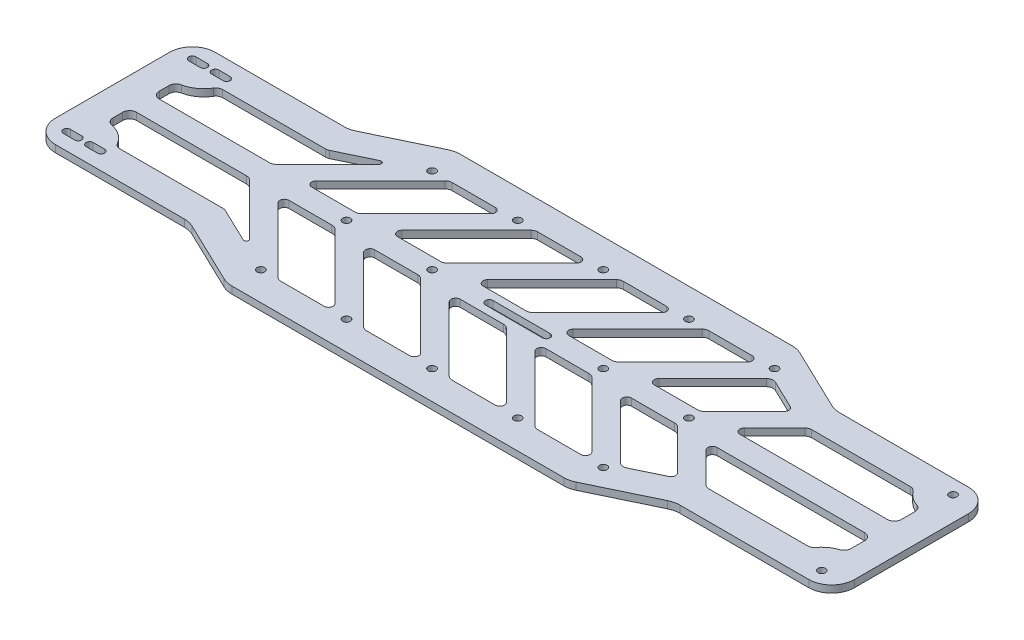
SolidWorks part; units mm, degrees
material "6061-T6 (SS)"
ref_plane "Front Plane" through (0, 0, 0) normal (0, 0, 1) x (1, 0, 0)
ref_plane "Top Plane" through (0, 0, 0) normal (0, 1, 0) x (1, 0, 0)
ref_plane "Right Plane" through (0, 0, 0) normal (1, 0, 0) x (0, 0, -1)
sketch "Sketch1" plane through (0, 0, 0) normal (0, 1, 0) x (1, 0, 0)
  line L1 (0, 0) -> (355.6, 0)
  line L2 (0, 0) -> (0, 101.6)
  line L3 (0, 101.6) -> (355.6, 101.6)
  line L4 (355.6, 0) -> (355.6, 101.6)
  dimension "D1" = 355.6
  dimension "D2" = 101.6
extrude "Boss-Extrude1" add sketch "Sketch1" along normal blind 3.175
sketch "Sketch2" plane through (0, 0, 0) normal (0, -1, 0) x (1, 0, 0)
  line L0 (0, -50.8) -> (355.6, -50.8) construction
  line L1 (0, -101.6) -> (0, 0) construction
  line L2 (355.6, 0) -> (355.6, -101.6) construction
  point P6 (10.16, -22.86)
  point P7 (344.8634, -21.59)
  point P8 (344.8634, -80.01)
  point P9 (10.16, -78.74)
  dimension "D1" = 55.88
  dimension "D2" = 58.42
  dimension "D3" = 334.7034
  dimension "D4" = 10.16
hole_wizard "M3 Clearance Hole2" positions "Sketch6" profile "Sketch5" hole size "M3" standard "ANSI Metric" end condition through all
sketch "Sketch6" plane through (0, 0, 0) normal (0, -1, 0) x (-1, 0, 0)
  point P0 (-344.8634, 21.59)
  point P3 (-344.8634, 80.01)
sketch "Sketch5" plane through (344.8634, 0, -21.59) normal (1, 0, 0) x (0, 0, -1)
  line L0 (0, 0) -> (0, 3.175)
  line L1 (0, 3.175) -> (1.7, 3.175)
  line L2 (1.7, 3.175) -> (1.7, 0)
  line L5 (1.7, 0) -> (0, 0)
  line L11 (0, -6.35) -> (0, 107.95) construction
  dimension "Thru Hole Dia." = 3.4
  dimension "Thru Hole Depth" = 3.175
sketch "Sketch7" plane through (0, 0, 0) normal (0, -1, 0) x (1, 0, 0)
  line L0 (7.62, -22.86) -> (12.7, -22.86) construction
  line L1 (7.62, -21.2838) -> (12.7, -21.2838)
  line L2 (7.62, -24.4362) -> (12.7, -24.4362)
  line L3 (0, -50.8) -> (34.1188, -50.8) construction
  line L4 (0, -50.8) -> (355.6, -50.8) construction
  line L5 (7.62, -78.74) -> (12.7, -78.74) construction
  line L6 (7.62, -80.3162) -> (12.7, -80.3162)
  line L7 (7.62, -77.1638) -> (12.7, -77.1638)
  arc A0 (7.62, -21.2838) -> (7.62, -24.4362) centre (7.62, -22.86) ccw
  arc A1 (12.7, -24.4362) -> (12.7, -21.2838) centre (12.7, -22.86) ccw
  arc A2 (7.62, -80.3162) -> (7.62, -77.1638) centre (7.62, -78.74) cw
  arc A3 (12.7, -77.1638) -> (12.7, -80.3162) centre (12.7, -78.74) cw
  point P2 (10.16, -22.86)
  point P15 (10.16, -78.74)
  dimension "D1" = 1.5762
  dimension "D2" = 5.08
extrude "Cut-Extrude1" cut sketch "Sketch7" against normal through all
sketch "Sketch16" plane through (0, 3.175, 0) normal (0, 1, 0) x (1, 0, 0)
  line L0 (355.6, 15.24) -> (285.75, 15.24)
  line L1 (355.6, 0) -> (355.6, 101.6) construction
  line L2 (0, 0) -> (355.6, 0) construction
  line L3 (355.6, 15.24) -> (355.6, 0)
  line L4 (355.6, 0) -> (254, 0)
  line L5 (285.75, 15.24) -> (254, 0)
  line L6 (355.6, 50.8) -> (0, 50.8) construction
  line L7 (0, 101.6) -> (0, 0) construction
  line L8 (177.8, 0) -> (177.8, 101.6) construction
  line L9 (355.6, 101.6) -> (0, 101.6) construction
  line L10 (69.85, 15.24) -> (101.6, 0)
  line L11 (0, 0) -> (101.6, 0)
  line L12 (0, 15.24) -> (0, 0)
  line L13 (0, 15.24) -> (69.85, 15.24)
  line L14 (0, 86.36) -> (69.85, 86.36)
  line L15 (0, 86.36) -> (0, 101.6)
  line L16 (0, 101.6) -> (101.6, 101.6)
  line L17 (69.85, 86.36) -> (101.6, 101.6)
  line L18 (285.75, 86.36) -> (254, 101.6)
  line L19 (355.6, 101.6) -> (254, 101.6)
  line L20 (355.6, 86.36) -> (355.6, 101.6)
  line L21 (355.6, 86.36) -> (285.75, 86.36)
  dimension "D1" = 15.24
  dimension "D2" = 101.6
  dimension "D3" = 69.85
extrude "Cut-Extrude3" cut sketch "Sketch16" against normal through all
fillet "Fillet1" radius 10.16 12 edges at (0, 1.5875, -86.36) (69.85, 1.5875, -86.36) (101.6, 1.5875, -101.6) (254, 1.5875, -101.6) (285.75, 1.5875, -86.36) (355.6, 1.5875, -86.36) (0, 1.5875, -15.24) (69.85, 1.5875, -15.24) (101.6, 1.5875, 0) (254, 1.5875, 0) (285.75, 1.5875, -15.24) (355.6, 1.5875, -15.24)
sketch "Sketch17" plane through (0, 3.175, 0) normal (0, 1, 0) x (1, 0, 0)
  line L0 (0, 50.8) -> (355.6, 50.8) construction
  line L1 (142.24, 88.9) -> (104.14, 50.8) construction
  line L2 (0, 50.8) -> (355.6, 50.8) construction
  line L3 (0, 76.2) -> (0, 25.4) construction
  line L4 (111.76, 88.9) -> (78.74, 55.88)
  line L5 (78.74, 55.88) -> (104.14, 55.88)
  line L6 (104.14, 55.88) -> (137.16, 88.9)
  line L7 (137.16, 88.9) -> (111.76, 88.9)
  line L8 (104.14, 88.9) -> (142.24, 88.9) construction
  line L9 (78.74, 45.72) -> (104.14, 45.72)
  line L10 (104.14, 45.72) -> (137.16, 12.7)
  line L11 (137.16, 12.7) -> (111.76, 12.7)
  line L12 (111.76, 12.7) -> (78.74, 45.72)
  line L13 (175.26, 88.9) -> (149.86, 88.9)
  line L14 (149.86, 88.9) -> (116.84, 55.88)
  line L15 (142.24, 55.88) -> (175.26, 88.9)
  line L16 (116.84, 55.88) -> (142.24, 55.88)
  line L17 (116.84, 45.72) -> (142.24, 45.72)
  line L18 (142.24, 45.72) -> (175.26, 12.7)
  line L19 (149.86, 12.7) -> (116.84, 45.72)
  line L20 (175.26, 12.7) -> (149.86, 12.7)
  line L21 (213.36, 88.9) -> (187.96, 88.9)
  line L22 (187.96, 88.9) -> (154.94, 55.88)
  line L23 (180.34, 55.88) -> (213.36, 88.9)
  line L24 (154.94, 55.88) -> (180.34, 55.88)
  line L25 (154.94, 45.72) -> (180.34, 45.72)
  line L26 (180.34, 45.72) -> (213.36, 12.7)
  line L27 (187.96, 12.7) -> (154.94, 45.72)
  line L28 (213.36, 12.7) -> (187.96, 12.7)
  line L29 (251.46, 88.9) -> (226.06, 88.9)
  line L30 (226.06, 88.9) -> (193.04, 55.88)
  line L31 (218.44, 55.88) -> (251.46, 88.9)
  line L32 (193.04, 55.88) -> (218.44, 55.88)
  line L33 (193.04, 45.72) -> (218.44, 45.72)
  line L34 (218.44, 45.72) -> (251.46, 12.7)
  line L35 (226.06, 12.7) -> (193.04, 45.72)
  line L36 (251.46, 12.7) -> (226.06, 12.7)
  line L37 (260.0411, 84.7811) -> (231.14, 55.88)
  line L38 (231.14, 55.88) -> (256.54, 55.88)
  line L39 (256.54, 55.88) -> (277.2032, 76.5432)
  line L40 (277.2032, 76.5432) -> (260.0411, 84.7811)
  line L41 (256.0844, 100.5995) -> (283.6656, 87.3605) construction
  line L42 (231.14, 45.72) -> (256.54, 45.72)
  line L43 (260.0411, 16.8189) -> (231.14, 45.72)
  line L44 (256.54, 45.72) -> (277.2032, 25.0568)
  line L45 (277.2032, 25.0568) -> (260.0411, 16.8189)
  line L46 (287.02, 73.66) -> (269.24, 55.88)
  line L47 (269.24, 55.88) -> (342.9, 55.88)
  line L48 (342.9, 55.88) -> (342.9, 67.4627)
  line L49 (287.02, 73.66) -> (333.8649, 73.66)
  line L51 (288.0621, 86.36) -> (345.44, 86.36) construction
  line L52 (355.6, 25.4) -> (355.6, 76.2) construction
  line L53 (269.24, 45.72) -> (342.9, 45.72)
  line L54 (342.9, 45.72) -> (342.9, 34.1373)
  line L55 (287.02, 27.94) -> (333.8649, 27.94)
  line L56 (287.02, 27.94) -> (269.24, 45.72)
  line L57 (12.7, 55.88) -> (66.04, 55.88)
  line L58 (66.04, 55.88) -> (86.36, 76.2)
  line L59 (72.7401, 73.66) -> (24.3397, 73.66)
  line L60 (12.7, 66.04) -> (12.7, 55.88)
  line L61 (10.16, 86.36) -> (67.5379, 86.36) construction
  line L62 (86.36, 76.2) -> (94.0476, 83.8876)
  line L63 (94.0476, 83.8876) -> (72.7401, 73.66)
  line L64 (71.9344, 87.3605) -> (99.5156, 100.5995) construction
  line L65 (12.7, 45.72) -> (66.04, 45.72)
  line L66 (86.36, 25.4) -> (94.0476, 17.7124)
  line L67 (66.04, 45.72) -> (86.36, 25.4)
  line L68 (94.0476, 17.7124) -> (72.7401, 27.94)
  line L69 (72.7401, 27.94) -> (24.3397, 27.94)
  line L70 (12.7, 35.56) -> (12.7, 45.72)
  arc A0 (342.9, 67.4627) -> (333.8649, 73.66) centre (344.8634, 80.01) cw
  circle A1 centre (344.8634, 80.01) radius 1.7 construction
  arc A2 (342.9, 34.1373) -> (333.8649, 27.94) centre (344.8634, 21.59) ccw
  arc A3 (24.3397, 73.66) -> (12.7, 66.04) centre (12.7, 78.74) cw
  arc A4 (12.7, 77.1638) -> (12.7, 80.3162) centre (12.7, 78.74) ccw construction
  arc A5 (24.3397, 27.94) -> (12.7, 35.56) centre (12.7, 22.86) ccw
  point P4 (104.14, 88.9)
  point P8 (104.14, 50.8)
  point P9 (104.14, 12.7)
  point P12 (142.24, 88.9)
  point P13 (142.24, 50.8)
  point P14 (142.24, 12.7)
  point P15 (180.34, 88.9)
  point P16 (180.34, 50.8)
  point P17 (180.34, 12.7)
  point P18 (218.44, 88.9)
  point P19 (218.44, 50.8)
  point P20 (218.44, 12.7)
  point P21 (256.54, 88.9)
  point P22 (256.54, 50.8)
  point P23 (256.54, 12.7)
  dimension "D13" = 12.7
  dimension "D17" = 12.7
  dimension "D1" = 38.1
  dimension "D2" = 104.14
  dimension "D4" = 45
  dimension "D5" = 5.08
  dimension "D6" = 25.4
  dimension "D7" = 7.62
  dimension "D9" = 38.1
  dimension "D10" = 38.1
  dimension "D11" = 12.7
  dimension "D12" = 12.7
  dimension "D14" = 12.7
  dimension "D15" = 12.7
  dimension "D16" = 38.1
  dimension "D18" = 12.7
  dimension "D19" = 38.1
  dimension "D3" = 5
  dimension "D8" = 4
hole_wizard "M3 Clearance Hole5" positions "Sketch19" profile "Sketch18" hole size "M3" standard "ANSI Metric" end condition through all
sketch "Sketch19" plane through (0, 3.175, 0) normal (0, 1, 0) x (1, 0, 0)
  point P0 (104.14, 88.9)
  point P3 (142.24, 88.9)
  point P6 (180.34, 88.9)
  point P9 (218.44, 88.9)
  point P12 (256.54, 88.9)
  point P15 (256.54, 12.7)
  point P18 (218.44, 12.7)
  point P21 (180.34, 12.7)
  point P24 (142.24, 12.7)
  point P27 (104.14, 12.7)
  point P30 (104.14, 50.8)
  point P33 (256.54, 50.8)
  point P36 (142.24, 50.8)
  point P39 (180.34, 50.8)
  point P42 (218.44, 50.8)
sketch "Sketch18" plane through (104.14, 3.175, -88.9) normal (1, 0, 0) x (0, 0, 1)
  line L0 (0, 0) -> (0, 3.175)
  line L1 (0, 3.175) -> (1.7, 3.175)
  line L2 (1.7, 3.175) -> (1.7, 0)
  line L5 (1.7, 0) -> (0, 0)
  line L11 (0, -6.35) -> (0, 107.95) construction
  dimension "Thru Hole Dia." = 3.4
  dimension "Thru Hole Depth" = 3.175
extrude "Cut-Extrude4" cut sketch "Sketch17" against normal through all
fillet "Fillet2" radius 2.032 16 edges at (137.16, 1.5875, -12.7) (175.26, 1.5875, -12.7) (213.36, 1.5875, -12.7) (251.46, 1.5875, -12.7) (251.46, 1.5875, -88.9) (213.36, 1.5875, -88.9) (175.26, 1.5875, -88.9) (137.16, 1.5875, -88.9) (193.04, 1.5875, -45.72) (154.94, 1.5875, -45.72) (116.84, 1.5875, -45.72) (78.74, 1.5875, -45.72) (193.04, 1.5875, -55.88) (154.94, 1.5875, -55.88) (116.84, 1.5875, -55.88) (78.74, 1.5875, -55.88)
fillet "Fillet3" radius 3.048 16 edges at (226.06, 1.5875, -12.7) (218.44, 1.5875, -45.72) (180.34, 1.5875, -45.72) (187.96, 1.5875, -12.7) (149.86, 1.5875, -12.7) (111.76, 1.5875, -12.7) (142.24, 1.5875, -45.72) (104.14, 1.5875, -45.72) (218.44, 1.5875, -55.88) (180.34, 1.5875, -55.88) (142.24, 1.5875, -55.88) (104.14, 1.5875, -55.88) (226.06, 1.5875, -88.9) (187.96, 1.5875, -88.9) (149.86, 1.5875, -88.9) (111.76, 1.5875, -88.9)
fillet "Fillet4" radius 3.048 5 edges at (72.7401, 1.5875, -73.66) (66.04, 1.5875, -55.88) (12.7, 1.5875, -55.88) (12.7, 1.5875, -66.04) (24.3397, 1.5875, -73.66)
fillet "Fillet5" radius 3.048 5 edges at (12.7, 1.5875, -35.56) (24.3397, 1.5875, -27.94) (72.7401, 1.5875, -27.94) (66.04, 1.5875, -45.72) (12.7, 1.5875, -45.72)
fillet "Fillet6" radius 3.048 12 edges at (342.9, 1.5875, -45.72) (342.9, 1.5875, -55.88) (342.9, 1.5875, -34.1373) (333.8649, 1.5875, -27.94) (342.9, 1.5875, -67.4627) (333.8649, 1.5875, -73.66) (287.02, 1.5875, -27.94) (287.02, 1.5875, -73.66) (260.0411, 1.5875, -84.7811) (256.54, 1.5875, -55.88) (256.54, 1.5875, -45.72) (260.0411, 1.5875, -16.8189)
fillet "Fillet7" radius 2.032 6 edges at (277.2032, 1.5875, -76.5432) (277.2032, 1.5875, -25.0568) (231.14, 1.5875, -55.88) (231.14, 1.5875, -45.72) (269.24, 1.5875, -55.88) (269.24, 1.5875, -45.72)
fillet "Fillet8" radius 1.016 2 edges at (94.0476, 1.5875, -83.8876) (94.0476, 1.5875, -17.7124)
sketch "Sketch20" plane through (0, 3.175, 0) normal (0, 1, 0) x (1, 0, 0)
  line L0 (167.64, 50.8) -> (193.04, 50.8) construction
  line L1 (0, 50.8) -> (355.6, 50.8) construction
  line L2 (167.64, 52.5) -> (193.04, 52.5)
  line L3 (167.64, 49.1) -> (193.04, 49.1)
  arc A0 (167.64, 52.5) -> (167.64, 49.1) centre (167.64, 50.8) ccw
  arc A1 (193.04, 49.1) -> (193.04, 52.5) centre (193.04, 50.8) ccw
  circle A2 centre (180.34, 50.8) radius 1.7 construction
  point P5 (180.34, 50.8)
  dimension "D1" = 25.4
extrude "Cut-Extrude5" cut sketch "Sketch20" against normal through all
pattern_linear "LPattern1" count 2 spacing 10.16 along (1, 0, 0) of "Cut-Extrude1"
